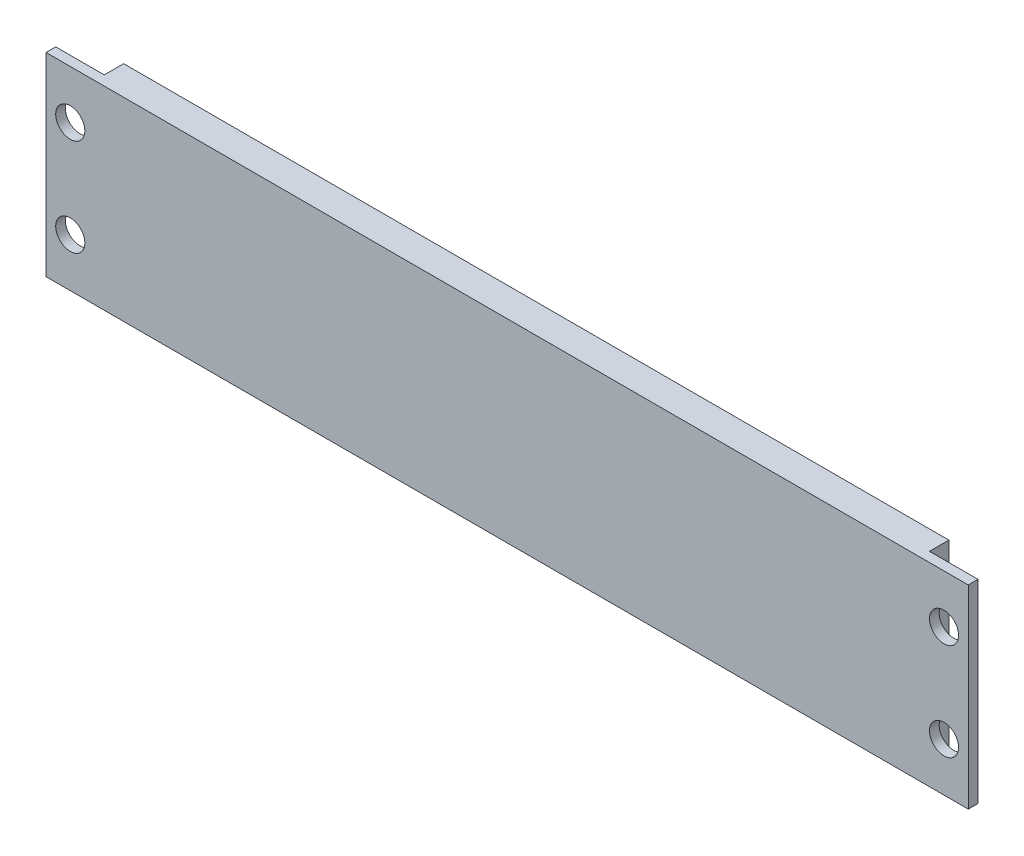
SolidWorks part; units mm, degrees
ref_plane "Спереди" through (0, 0, 0) normal (0, 0, 1) x (1, 0, 0)
ref_plane "Сверху" through (0, 0, 0) normal (0, 1, 0) x (1, 0, 0)
ref_plane "Справа" through (0, 0, 0) normal (1, 0, 0) x (0, 0, -1)
ref_plane "Плоскость4"
sketch "Эскиз1" plane through (0, 0, 0) normal (0, 0, 1) x (1, 0, 0)
  line L0 (85, 0) -> (85, 20)
  line L1 (85, 20) -> (0, 20)
  line L2 (0, 20) -> (0, 0)
  line L3 (0, 0) -> (85, 0)
  dimension "D1" = 85
  dimension "D2" = 20
extrude "Выдавливание1" add sketch "Эскиз1" along normal blind 3
sketch "Эскиз2" plane through (0, 0, 3) normal (0, 0, 1) x (1, 0, 0)
  line L0 (90, 0) -> (90, 20)
  line L1 (90, 20) -> (85, 20)
  line L2 (85, 20) -> (85, 0)
  line L3 (85, 0) -> (90, 0)
  line L4 (0, 0) -> (0, 20)
  line L5 (0, 20) -> (-5, 20)
  line L6 (-5, 20) -> (-5, 0)
  line L7 (-5, 0) -> (0, 0)
  circle A0 centre (87.5, 5) radius 1.5
  circle A1 centre (87.5, 15) radius 1.5
  circle A2 centre (-2.5, 5) radius 1.5
  circle A3 centre (-2.5, 15) radius 1.5
  line M2 (85, 0) -> (85, 20)
  line M4 (0, 20) -> (0, 0)
  dimension "D2" = 3
  dimension "D3" = 3
  dimension "D1" = 5
extrude "Выдавливание2" add sketch "Эскиз2" against normal blind 1 contours L3 L0 L1 A1 A0 M2 | L6 L7 L5 A3 A2 M4
